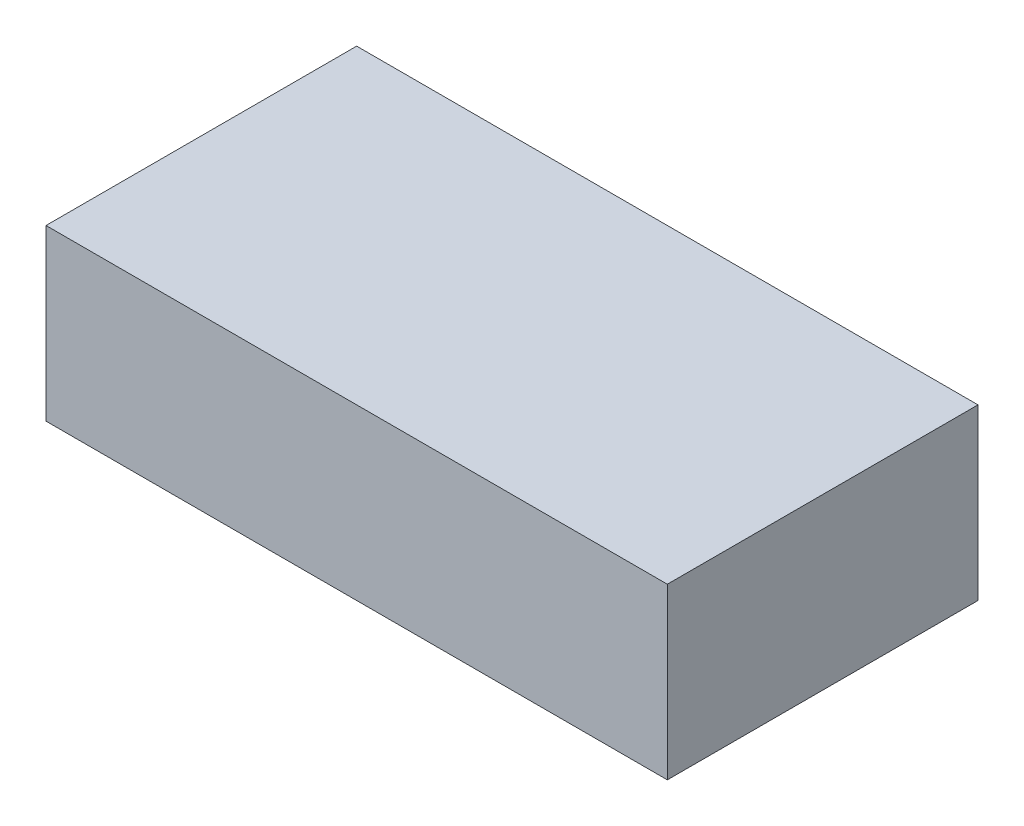
SolidWorks part; units mm, degrees
ref_plane "前视基准面" through (0, 0, 0) normal (0, 0, 1) x (1, 0, 0)
ref_plane "上视基准面" through (0, 0, 0) normal (0, 1, 0) x (1, 0, 0)
ref_plane "右视基准面" through (0, 0, 0) normal (1, 0, 0) x (0, 0, -1)
sketch "草图1" plane through (0, 0, 0) normal (0, 1, 0) x (1, 0, 0)
  line L1 (-55, 27.5) -> (55, 27.5)
  line L2 (-55, 27.5) -> (-55, -27.5)
  line L3 (-55, -27.5) -> (55, -27.5)
  line L4 (55, 27.5) -> (55, -27.5)
  line L5 (-55, 27.5) -> (55, -27.5) construction
  line L6 (-55, -27.5) -> (55, 27.5) construction
  point P0 (0, 0)
  dimension "D1" = 55
  dimension "D2" = 110
extrude "凸台-拉伸1" add sketch "草图1" along normal blind 30
